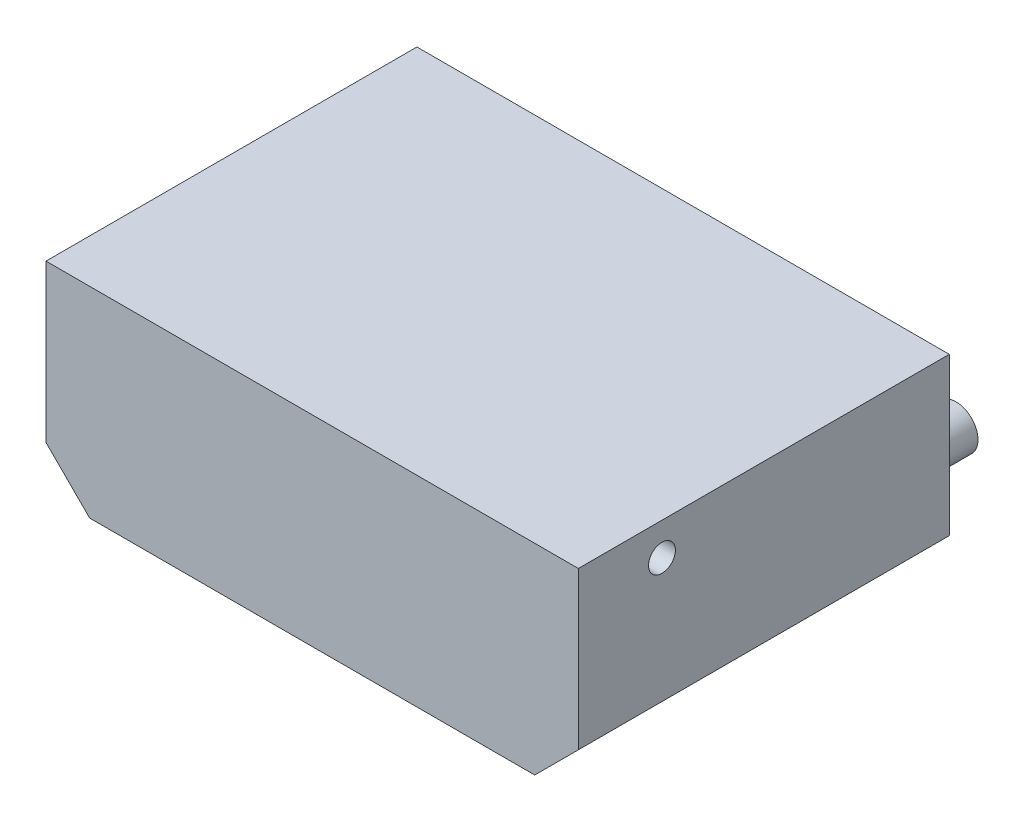
SolidWorks part; units mm, degrees
ref_plane "Front Plane" through (0, 0, 0) normal (0, 0, 1) x (1, 0, 0)
ref_plane "Top Plane" through (0, 0, 0) normal (0, 1, 0) x (1, 0, 0)
ref_plane "Right Plane" through (0, 0, 0) normal (1, 0, 0) x (0, 0, -1)
sketch "Sketch1" plane through (0, 0, 0) normal (0, 0, 1) x (1, 0, 0)
  line L0 (-102, -46) -> (-122, -26)
  line L1 (102, -46) -> (-102, -46)
  line L2 (122, -26) -> (122, 46)
  line L3 (122, 46) -> (-122, 46)
  line L4 (-122, -26) -> (-122, 46)
  line L5 (122, -46) -> (-122, 46) construction
  line L6 (122, 46) -> (-122, -46) construction
  line L7 (122, -26) -> (102, -46)
  point P0 (0, 0)
  dimension "D1" = 244
  dimension "D2" = 92
extrude "Boss-Extrude1" add sketch "Sketch1" along normal blind 170
sketch "Sketch2" plane through (0, -46, 0) normal (0, -1, 0) x (1, 0, 0)
  line L0 (-102, 85) -> (102, 85) construction
  line L1 (-102, 170) -> (-102, 0) construction
  line L2 (102, 170) -> (102, 0) construction
  line L3 (-102, 170) -> (102, 170) construction
  line L4 (87, 15) -> (-87, 15)
  line L5 (87, 15) -> (87, 155)
  line L6 (87, 155) -> (-87, 155)
  line L7 (-87, 15) -> (-87, 155)
  line L8 (87, 15) -> (-87, 155) construction
  line L9 (87, 155) -> (-87, 15) construction
  point P6 (0, 85)
  dimension "D1" = 15
  dimension "D2" = 15
extrude "Cut-Extrude1" cut sketch "Sketch2" against normal blind 0.1
sketch "Sketch3" plane through (0, 0, 0) normal (0, 0, -1) x (-1, 0, 0)
  line L0 (-46.4443, 46) -> (-46.4443, -46) construction
  line L1 (-122, 46) -> (122, 46) construction
  line L2 (102, -46) -> (-102, -46) construction
  circle A0 centre (-76.4755, 0) radius 10
  circle A1 centre (-106.4755, 0) radius 10
  circle A2 centre (-16.4131, 0) radius 10
  circle A3 centre (13.5869, 0) radius 10
  dimension "D1" = 20
  dimension "D2" = 20
  dimension "D3" = 30
extrude "Boss-Extrude2" add sketch "Sketch3" along normal blind 18.7
sketch "Sketch4" plane through (0, -45.9, 0) normal (0, -1, 0) x (1, 0, 0)
  text T0 "<b>VIDEOJET</b>" font "Times New Roman" height in points 72
extrude "Cut-Extrude2" cut sketch "Sketch4" against normal blind 0.1
sketch "Sketch5" plane through (122, 0, 0) normal (1, 0, 0) x (0, 0, -1)
  circle A0 centre (-131.6684, 31.0703) radius 6.1604
extrude "Cut-Extrude3" cut sketch "Sketch5" against normal up to next
